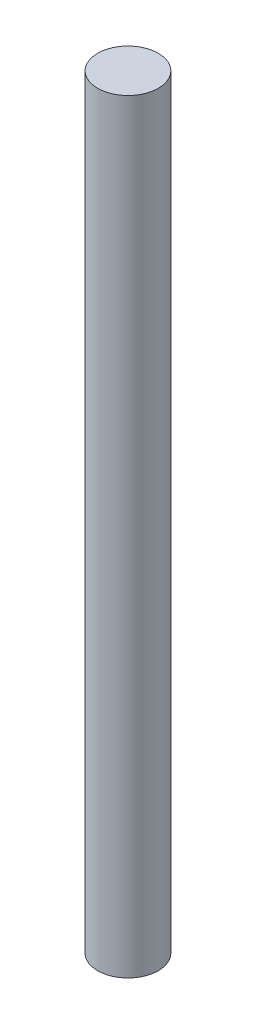
SolidWorks part; units mm, degrees
ref_plane "Front" through (0, 0, 0) normal (0, 0, 1) x (1, 0, 0)
ref_plane "Top" through (0, 0, 0) normal (0, 1, 0) x (1, 0, 0)
ref_plane "Right" through (0, 0, 0) normal (1, 0, 0) x (0, 0, -1)
sketch "Sketch1" plane through (0, 0, 0) normal (0, 1, 0) x (1, 0, 0)
  circle A0 centre (0, 0) radius 3.175
  dimension "D1" = 6.35
extrude "Boss-Extrude1" add sketch "Sketch1" along normal blind 80
